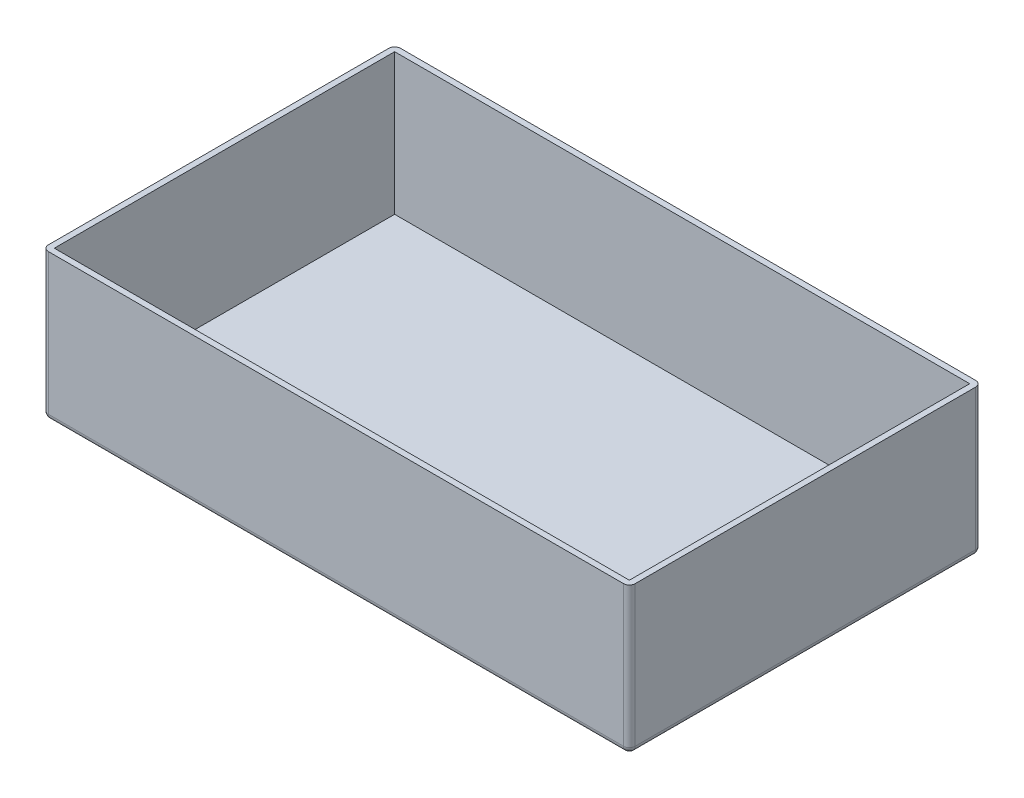
SolidWorks part; units mm, degrees
ref_plane "Front Plane" through (0, 0, 0) normal (0, 0, 1) x (1, 0, 0)
ref_plane "Top Plane" through (0, 0, 0) normal (0, 1, 0) x (1, 0, 0)
ref_plane "Right Plane" through (0, 0, 0) normal (1, 0, 0) x (0, 0, -1)
sketch "Sketch1" plane through (0, 0, 0) normal (0, 1, 0) x (1, 0, 0)
  line L1 (-100, 60) -> (100, 60)
  line L2 (-100, 60) -> (-100, -60)
  line L3 (-100, -60) -> (100, -60)
  line L4 (100, 60) -> (100, -60)
  line L5 (-100, 60) -> (100, -60) construction
  line L6 (-100, -60) -> (100, 60) construction
  point P0 (0, 0)
  dimension "D1" = 120
  dimension "D2" = 200
extrude "Boss-Extrude1" add sketch "Sketch1" along normal blind 50
shell "Shell2" thickness 2
fillet "Fillet1" radius 2 8 edges at (0, 0, -60) (-100, 0, 0) (0, 0, 60) (100, 0, 0) (100, 25, 60) (-100, 25, 60) (-100, 25, -60) (100, 25, -60)
